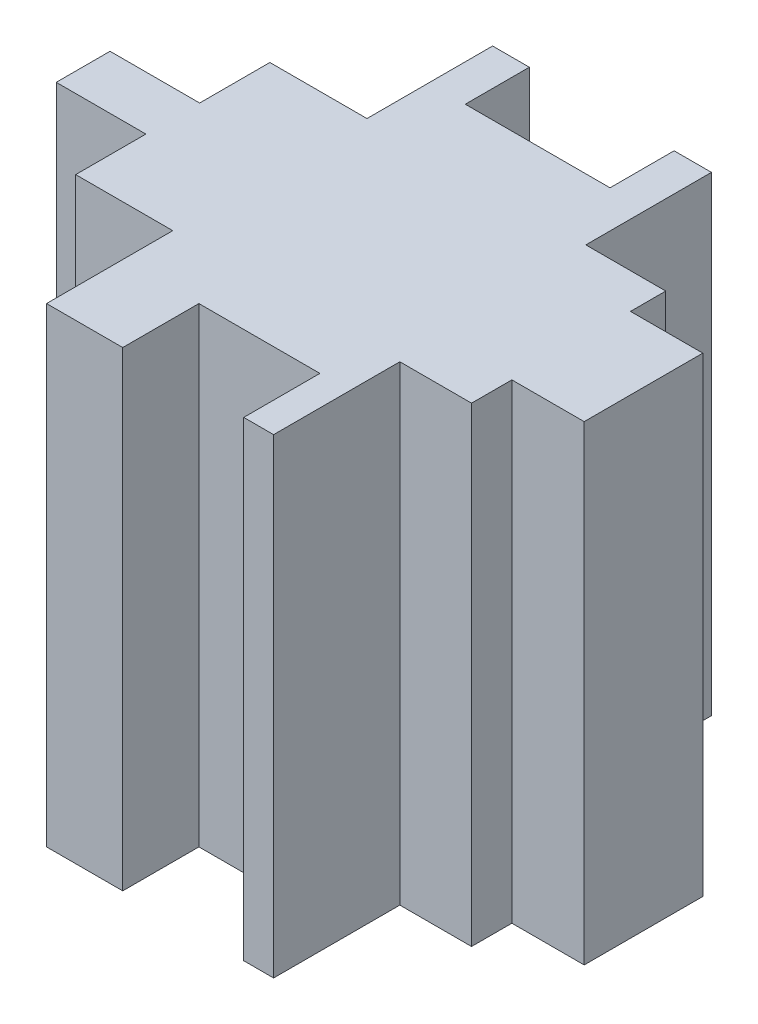
SolidWorks part; units mm, degrees
ref_plane "Front Plane"
ref_plane "Top Plane" through (0, 0, 0) normal (0, 1, 0) x (1, 0, 0)
ref_plane "Right Plane" through (0, 0, 0) normal (1, 0, 0) x (0, 0, -1)
sketch "Sketch1" plane through (0, 0, 0) normal (0, 1, 0) x (1, 0, 0)
  line L0 (537.21, 330.2) -> (673.1, 330.2)
  line L1 (0, 0) -> (165.1, 0)
  line L2 (0, 0) -> (0, 119.38)
  line L3 (0, 330.2) -> (165.1, 330.2)
  line L4 (673.1, 0) -> (673.1, 68.58)
  line L5 (0, 119.38) -> (-152.4, 119.38)
  line L7 (0, 210.82) -> (-152.4, 210.82)
  line L8 (-152.4, 119.38) -> (-152.4, 210.82)
  line L9 (673.1, 270.256) -> (796.036, 270.256)
  line L11 (673.1, 68.58) -> (796.036, 68.58)
  line L12 (796.036, 270.256) -> (796.036, 68.58)
  line L14 (165.1, 0) -> (165.1, -85.09)
  line L15 (294.64, -85.09) -> (500.38, -85.09)
  line L16 (551.18, 0) -> (551.18, -85.09)
  line L18 (165.1, -85.09) -> (165.1, -214.63)
  line L19 (165.1, -214.63) -> (294.64, -214.63)
  line L20 (294.64, -85.09) -> (294.64, -214.63)
  line L26 (165.1, 330.2) -> (165.1, 434.848)
  line L27 (227.584, 434.848) -> (473.71, 434.848)
  line L28 (537.21, 330.2) -> (537.21, 434.848)
  line L30 (165.1, 434.848) -> (165.1, 543.814)
  line L31 (165.1, 543.814) -> (227.584, 543.814)
  line L32 (227.584, 434.848) -> (227.584, 543.814)
  line L34 (537.21, 434.848) -> (537.21, 543.814)
  line L35 (537.21, 543.814) -> (473.71, 543.814)
  line L36 (473.71, 434.848) -> (473.71, 543.814)
  line L38 (551.18, -85.09) -> (551.18, -214.63)
  line L39 (551.18, -214.63) -> (500.38, -214.63)
  line L40 (500.38, -85.09) -> (500.38, -214.63)
  line L41 (673.1, 270.256) -> (673.1, 330.2)
  line L42 (551.18, 0) -> (673.1, 0)
  line L43 (0, 210.82) -> (0, 330.2)
  dimension "D1" = 91.44
  dimension "D2" = 119.38
  dimension "D3" = 330.2
  dimension "D4" = 673.1
  dimension "D5" = 104.648
  dimension "D6" = 108.966
  dimension "D7" = 63.5
  dimension "D8" = 62.484
  dimension "D9" = 372.11
  dimension "D10" = 165.1
  dimension "D11" = 201.676
  dimension "D12" = 122.936
  dimension "D13" = 68.58
  dimension "D14" = 85.09
  dimension "D15" = 165.1
  dimension "D16" = 129.54
  dimension "D17" = 129.54
  dimension "D18" = 50.8
  dimension "D19" = 386.08
  dimension "D20" = 152.4
  dimension "D21" = 108.966
extrude "Boss-Extrude1" add sketch "Sketch1" along normal blind 800.1
